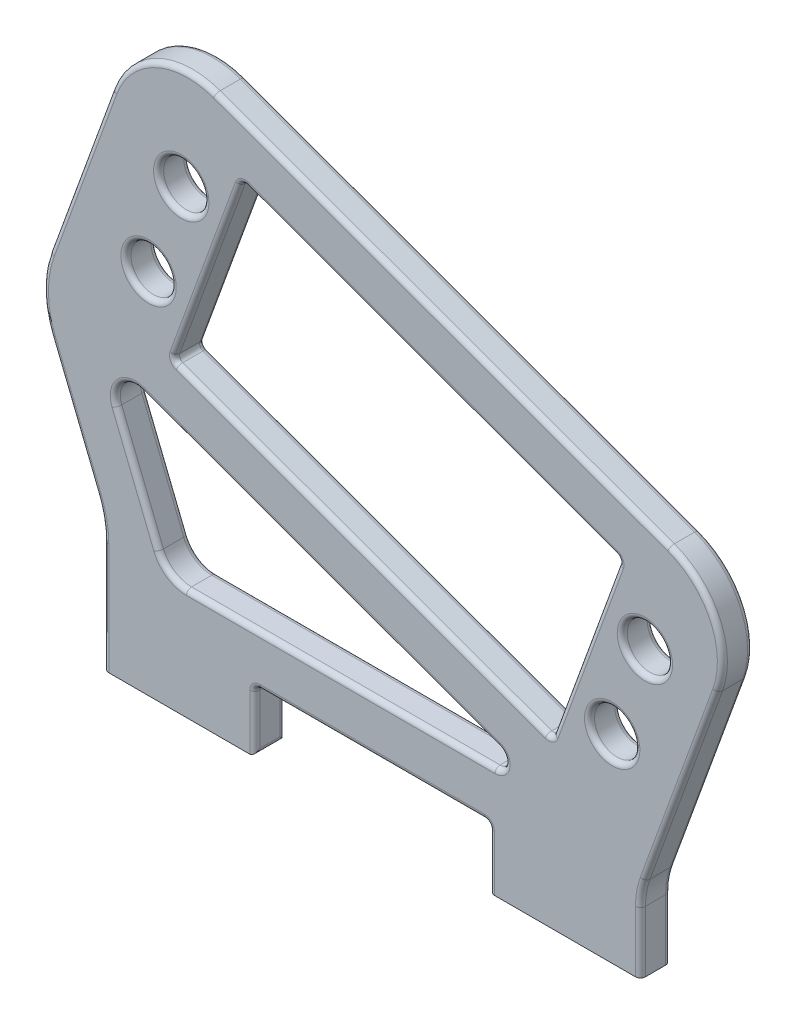
SolidWorks part; units mm, degrees
ref_plane "Front Plane" through (0, 0, 0) normal (0, 0, 1) x (1, 0, 0)
ref_plane "Top Plane" through (0, 0, 0) normal (0, 1, 0) x (1, 0, 0)
ref_plane "Right Plane" through (0, 0, 0) normal (1, 0, 0) x (0, 0, -1)
sketch "Sketch1" plane through (0, 0, 0) normal (0, 0, 1) x (1, 0, 0)
  line L0 (0, 0) -> (15, 0)
  line L1 (15, 0) -> (15, 6)
  line L2 (15, 6) -> (38.3, 6)
  line L3 (38.3, 6) -> (38.3, 0)
  line L4 (38.3, 0) -> (53.3, 0)
  line L5 (53.3, 0) -> (53.3, 7.3867)
  line L6 (6.8829, 30.0233) -> (13.7233, 48.8171)
  line L7 (13.7233, 48.8171) -> (51.311, 35.1363)
  line L8 (0, 0) -> (0, 13)
  line L9 (51.311, 35.1363) -> (44.4706, 16.3425)
  line L10 (44.4706, 16.3425) -> (6.8829, 30.0233)
  line L11 (47.8908, 25.7394) -> (10.3031, 39.4202) construction
  line L12 (53.3, 7.3867) -> (63.696, 35.9494)
  line L13 (63.696, 35.9494) -> (3.5557, 57.8387)
  line L14 (29.0969, 32.5798) -> (32.5171, 41.9767) construction
  line L21 (3.5557, 57.8387) -> (-6.7049, 29.6479)
  line L22 (0, 13) -> (-6.7049, 29.6479)
  circle A0 centre (19.7, 36) radius 2.1 construction
  circle A1 centre (19.7, 36) radius 10 construction
  circle A6 centre (7.6991, 45.4228) radius 2.25
  circle A7 centre (4.4499, 36.4958) radius 2.25
  circle A8 centre (53.744, 28.6638) radius 2.25
  circle A9 centre (50.4948, 19.7368) radius 2.25
  dimension "D5" = 4.2
  dimension "D7" = 20
  dimension "D10" = 40
  dimension "D12" = 20
  dimension "D13" = 64
  dimension "D19" = 4.5
  dimension "D20" = 4.75
  dimension "D21" = 24.5
  dimension "D1" = 15
  dimension "D2" = 6
  dimension "D3" = 23.3
  dimension "D4" = 15
  dimension "D6" = 36
  dimension "D8" = 19.7
  dimension "D9" = 13
  dimension "D11" = 20
  dimension "D22" = 5
  dimension "D23" = 12.64
  dimension "D24" = 30
extrude "Boss-Extrude1" add sketch "Sketch1" along normal blind 3
fillet "Fillet1" radius 8 2 edges at (63.696, 35.9494, 1.5) (3.5557, 57.8387, 1.5)
fillet "Fillet2" radius 10 2 edges at (0, 13, 1.5) (-6.7049, 29.6479, 1.5)
fillet "Fillet3" radius 7.5 1 edges at (53.3, 7.3867, 1.5)
sketch "Sketch3" plane through (0, 0, 3) normal (0, 0, 1) x (1, 0, 0)
  line L13 (15, 11) -> (38.3, 11)
  line L14 (8.2217, 11) -> (38.8586, 11)
  line L16 (-0.6353, 27.961) -> (3.9139, 16.6657)
  line L17 (1.2869, 23.1884) -> (5.4389, 12.8792)
  line L19 (5.1728, 25.3248) -> (42.7605, 11.644)
  line L20 (3.8262, 25.8149) -> (39.2006, 12.9397)
  arc A5 (39.2006, 12.9397) -> (38.8586, 11) centre (38.8586, 12) cw
  arc A6 (8.2217, 11) -> (5.4389, 12.8792) centre (8.2217, 14) cw
  arc A7 (1.2869, 23.1884) -> (3.8262, 25.8149) centre (3.1421, 23.9356) cw
  dimension "D4" = 1
  dimension "D5" = 3
  dimension "D6" = 2
  dimension "D1" = 5
  dimension "D2" = 5
  dimension "D3" = 5
extrude "Cut-Extrude1" cut sketch "Sketch3" against normal blind 10
fillet "Fillet4" radius 0.5 64 edges at (39.8434, 11.8264, 3) (23.5401, 11, 3) (6.5428, 11.5138, 3) (3.3629, 18.0338, 3) (1.7042, 25.3257, 3) (1.7042, 25.3257, 0) (3.3629, 18.0338, 0) (6.5428, 11.5138, 0) (23.5401, 11, 0) (39.8434, 11.8264, 0) (0, 5.5309, 0) (53.3, 3.0321, 0) (53.4139, 7.3666, 0) (57.3561, 18.5306, 0) (60.6927, 34.549, 0) (33.6258, 46.8941, 0) (4.9561, 54.8355, 0) (-2.2874, 41.7852, 0) (-5.9959, 29.6599, 0) (-2.9986, 20.4454, 0) (53.3, 3.0321, 3) (53.4139, 7.3666, 3) (57.3561, 18.5306, 3) (60.6927, 34.549, 3) (33.6258, 46.8941, 3) (4.9561, 54.8355, 3) (-2.2874, 41.7852, 3) (-5.9959, 29.6599, 3) (-2.9986, 20.4454, 3) (0, 5.5309, 3) (32.5171, 41.9767, 3) (32.5171, 41.9767, 0) (25.6767, 23.1829, 3) (25.6767, 23.1829, 0) (51.494, 28.6638, 0) (51.494, 28.6638, 3) (51.311, 35.1363, 1.5) (47.8908, 25.7394, 3) (44.4706, 16.3425, 1.5) (47.8908, 25.7394, 0) (6.8829, 30.0233, 1.5) (10.3031, 39.4202, 3) (13.7233, 48.8171, 1.5) (10.3031, 39.4202, 0) (52.7448, 19.7368, 0) (52.7448, 19.7368, 3) (2.1999, 36.4958, 0) (2.1999, 36.4958, 3) (15, 0, 1.5) (15, 3, 3) (15, 3, 0) (15, 6, 1.5) (26.65, 6, 3) (26.65, 6, 0) (38.3, 6, 1.5) (38.3, 3, 3) (38.3, 0, 1.5) (38.3, 3, 0) (21.5134, 19.3773, 3) (21.5134, 19.3773, 0) (-0.1827, 12.9646, 0) (-0.1827, 12.9646, 3) (9.9491, 45.4228, 0) (9.9491, 45.4228, 3)
